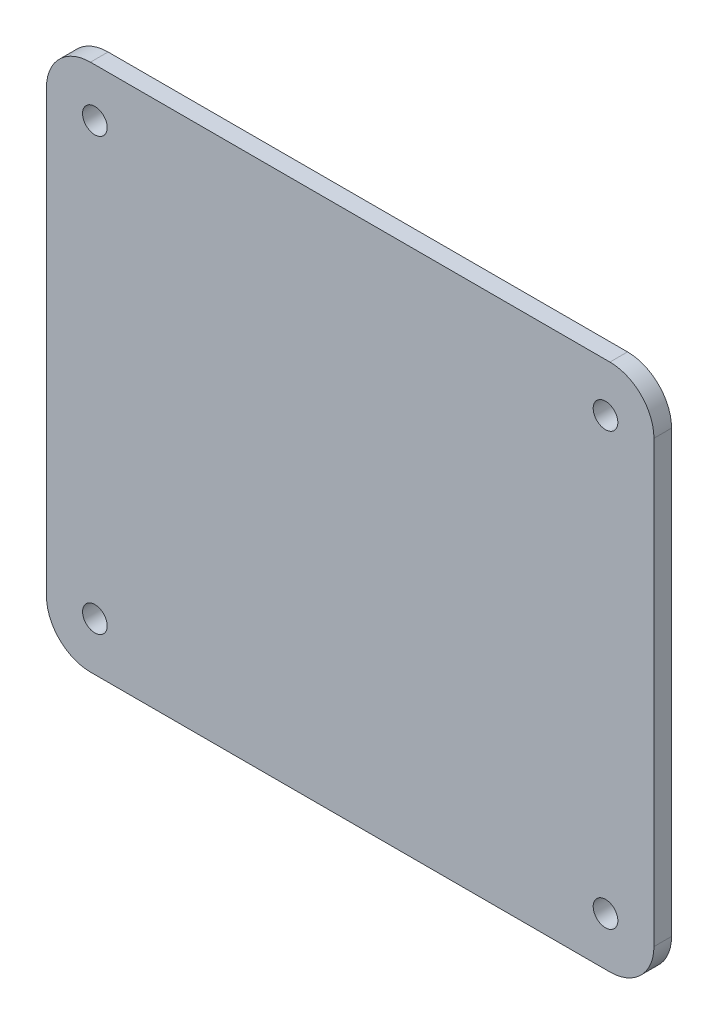
SolidWorks part; units mm, degrees
ref_plane "Front Plane" through (0, 0, 0) normal (0, 0, 1) x (1, 0, 0)
ref_plane "Top Plane" through (0, 0, 0) normal (0, 1, 0) x (1, 0, 0)
ref_plane "Right Plane" through (0, 0, 0) normal (1, 0, 0) x (0, 0, -1)
sketch3d "3DSketch1" plane through (0, 0, 0) normal (0, 0, 1) x (1, 0, 0)
sketch "Sketch3" plane through (0, 0, 55.2909) normal (0, 0, 1) x (1, 0, 0)
  line L20 (40.7272, 62.8578) -> (-18.2728, 62.8578)
  line L21 (-21.7728, 59.3578) -> (-21.7728, 9.3578)
  line L22 (-18.2728, 5.8578) -> (40.7272, 5.8578)
  line L23 (44.2272, 9.3578) -> (44.2272, 59.3578)
  line L24 (40.7272, 62.8578) -> (-18.2728, 62.8578)
  line L25 (-21.7728, 59.3578) -> (-21.7728, 9.3578)
  line L26 (-18.2728, 5.8578) -> (40.7272, 5.8578)
  line L27 (44.2272, 9.3578) -> (44.2272, 59.3578)
  line L44 (-23.2728, 59.3578) -> (-23.2728, 9.3578)
  line L45 (-18.2728, 4.3578) -> (40.7272, 4.3578)
  line L46 (45.7272, 9.3578) -> (45.7272, 59.3578)
  line L47 (40.7272, 64.3578) -> (-18.2728, 64.3578)
  line L48 (-23.2728, 59.3578) -> (-23.2728, 9.3578)
  line L49 (-18.2728, 4.3578) -> (40.7272, 4.3578)
  line L50 (45.7272, 9.3578) -> (45.7272, 59.3578)
  line L51 (40.7272, 64.3578) -> (-18.2728, 64.3578)
  arc A25 (-18.2728, 62.8578) -> (-21.7728, 59.3578) centre (-18.2728, 59.3578) ccw
  arc A26 (-21.7728, 9.3578) -> (-18.2728, 5.8578) centre (-18.2728, 9.3578) ccw
  arc A27 (40.7272, 5.8578) -> (44.2272, 9.3578) centre (40.7272, 9.3578) ccw
  arc A28 (44.2272, 59.3578) -> (40.7272, 62.8578) centre (40.7272, 59.3578) ccw
  arc A29 (-18.2728, 62.8578) -> (-21.7728, 59.3578) centre (-18.2728, 59.3578) ccw
  arc A30 (-21.7728, 9.3578) -> (-18.2728, 5.8578) centre (-18.2728, 9.3578) ccw
  arc A31 (40.7272, 5.8578) -> (44.2272, 9.3578) centre (40.7272, 9.3578) ccw
  arc A32 (44.2272, 59.3578) -> (40.7272, 62.8578) centre (40.7272, 59.3578) ccw
  arc A53 (-23.2728, 9.3578) -> (-18.2728, 4.3578) centre (-18.2728, 9.3578) ccw
  arc A54 (40.7272, 4.3578) -> (45.7272, 9.3578) centre (40.7272, 9.3578) ccw
  arc A55 (45.7272, 59.3578) -> (40.7272, 64.3578) centre (40.7272, 59.3578) ccw
  arc A56 (-18.2728, 64.3578) -> (-23.2728, 59.3578) centre (-18.2728, 59.3578) ccw
  arc A57 (-23.2728, 9.3578) -> (-18.2728, 4.3578) centre (-18.2728, 9.3578) ccw
  arc A58 (40.7272, 4.3578) -> (45.7272, 9.3578) centre (40.7272, 9.3578) ccw
  arc A59 (45.7272, 59.3578) -> (40.7272, 64.3578) centre (40.7272, 59.3578) ccw
  arc A60 (-18.2728, 64.3578) -> (-23.2728, 59.3578) centre (-18.2728, 59.3578) ccw
  dimension "D1" = 0.5
  dimension "D2" = 2
extrude "Boss-Extrude1" add sketch "Sketch3" along normal blind 6.5
sketch "Sketch5" plane through (0, 0, 55.2909) normal (0, 0, 1) x (1, 0, 0)
  line L0 (44.2272, 34.3578) -> (-21.7728, 34.3578) construction
  line L1 (44.2272, 9.3578) -> (44.2272, 59.3578) construction
  line L2 (-21.7728, 59.3578) -> (-21.7728, 9.3578) construction
  line L3 (11.2272, 62.8578) -> (11.2272, 5.8578) construction
  line L4 (40.7272, 62.8578) -> (-18.2728, 62.8578) construction
  line L5 (-18.2728, 5.8578) -> (40.7272, 5.8578) construction
  circle A0 centre (-17.7728, 58.8578) radius 3
  circle A1 centre (40.2272, 58.8578) radius 3
  circle A2 centre (-17.7728, 9.8578) radius 3
  circle A3 centre (40.2272, 9.8578) radius 3
  circle A4 centre (-17.7728, 9.8578) radius 1.4
  circle A5 centre (-17.7728, 58.8578) radius 1.4
  circle A6 centre (40.2272, 58.8578) radius 1.4
  circle A7 centre (40.2272, 9.8578) radius 1.4
sketch "Sketch6" plane through (0, 4.3578, 0) normal (0, -1, 0) x (1, 0, 0)
  line L0 (40.7272, 58.5409) -> (28.2272, 58.5409) construction
  line L1 (40.7272, 61.7909) -> (40.7272, 55.2909) construction
  line L2 (28.2272, 61.7909) -> (28.2272, 59.5909)
  line L3 (-18.2728, 61.7909) -> (40.7272, 61.7909) construction
  line L4 (28.2272, 59.5909) -> (36.2272, 59.5909)
  line L5 (40.7272, 61.5285) -> (32.2272, 61.5285) construction
  line L6 (36.2272, 59.5909) -> (36.2272, 61.7909)
  line L7 (36.2272, 61.7909) -> (28.2272, 61.7909)
sketch "Sketch7" plane through (0, 4.3578, 0) normal (0, -1, 0) x (1, 0, 0)
  line L0 (-18.2728, 58.5409) -> (18.7272, 58.5409) construction
  line L1 (-18.2728, 61.7909) -> (-18.2728, 55.2909) construction
  line L7 (18.7272, 61.7909) -> (18.7272, 59.7909)
  line L8 (18.7272, 59.7909) -> (2.7272, 59.7909)
  line L9 (2.7272, 59.7909) -> (2.7272, 61.7909)
  line L10 (-18.2728, 61.7909) -> (40.7272, 61.7909) construction
  line L11 (2.7272, 61.7909) -> (18.7272, 61.7909)
sketch "Sketch8" plane through (0, 4.3578, 0) normal (0, -1, 0) x (1, 0, 0)
  line L0 (-18.2728, 58.5409) -> (-6.1728, 58.5409) construction
  line L1 (-18.2728, 61.7909) -> (-18.2728, 55.2909) construction
  line L7 (-6.1728, 61.7909) -> (-6.1728, 58.9909)
  line L8 (-18.2728, 61.7909) -> (40.7272, 61.7909) construction
  line L9 (-6.1728, 58.9909) -> (-15.1728, 58.9909)
  line L10 (-15.1728, 58.9909) -> (-15.1728, 61.7909)
  line L11 (-15.1728, 61.7909) -> (-6.1728, 61.7909)
sketch "Sketch9" plane through (45.7272, 0, 0) normal (1, 0, 0) x (0, 0, -1)
  line L0 (-58.5409, 9.3578) -> (-58.5409, 45.8078) construction
  line L1 (-61.7909, 9.3578) -> (-55.2909, 9.3578) construction
  line L3 (-59.7909, 45.3078) -> (-59.7909, 29.8078)
  line L9 (-59.7909, 29.8078) -> (-61.7909, 29.8078)
  line L10 (-61.7909, 9.3578) -> (-61.7909, 59.3578) construction
  line L12 (-61.7909, 45.3078) -> (-59.7909, 45.3078)
  line L13 (-61.7909, 45.3078) -> (-61.7909, 29.8078)
sketch "Sketch10" plane through (-23.2728, 0, 0) normal (-1, 0, 0) x (0, 0, 1)
  line L0 (58.5409, 9.3578) -> (58.5409, 42.6578) construction
  line L1 (61.7909, 9.3578) -> (55.2909, 9.3578) construction
  line L2 (55.2909, 42.6578) -> (59.2909, 42.6578)
  line L3 (55.2909, 59.3578) -> (55.2909, 9.3578) construction
  line L4 (59.2909, 42.6578) -> (59.2909, 26.6578)
  line L5 (59.2909, 26.6578) -> (55.2909, 26.6578)
  line L6 (55.2909, 26.6578) -> (55.2909, 42.6578)
sketch "Sketch11" plane through (0, 0, 55.2909) normal (0, 0, 1) x (1, 0, 0)
  line L25 (-23.2728, 26.6578) -> (-23.2728, 42.6578)
  line L30 (-23.2728, 26.6578) -> (-23.2728, 9.3578)
  line L31 (-18.2728, 4.3578) -> (40.7272, 4.3578)
  line L32 (-23.2728, 59.3578) -> (-23.2728, 42.6578)
  line L33 (40.7272, 64.3578) -> (-18.2728, 64.3578)
  line L34 (45.7272, 9.3578) -> (45.7272, 59.3578)
  line L35 (-23.2728, 26.6578) -> (-23.2728, 9.3578)
  line L36 (-18.2728, 4.3578) -> (40.7272, 4.3578)
  line L37 (-23.2728, 59.3578) -> (-23.2728, 42.6578)
  line L38 (40.7272, 64.3578) -> (-18.2728, 64.3578)
  line L39 (45.7272, 9.3578) -> (45.7272, 59.3578)
  arc A31 (-23.2728, 9.3578) -> (-18.2728, 4.3578) centre (-18.2728, 9.3578) ccw
  arc A32 (-18.2728, 64.3578) -> (-23.2728, 59.3578) centre (-18.2728, 59.3578) ccw
  arc A33 (45.7272, 59.3578) -> (40.7272, 64.3578) centre (40.7272, 59.3578) ccw
  arc A34 (40.7272, 4.3578) -> (45.7272, 9.3578) centre (40.7272, 9.3578) ccw
  arc A35 (-23.2728, 9.3578) -> (-18.2728, 4.3578) centre (-18.2728, 9.3578) ccw
  arc A36 (-18.2728, 64.3578) -> (-23.2728, 59.3578) centre (-18.2728, 59.3578) ccw
  arc A37 (45.7272, 59.3578) -> (40.7272, 64.3578) centre (40.7272, 59.3578) ccw
  arc A38 (40.7272, 4.3578) -> (45.7272, 9.3578) centre (40.7272, 9.3578) ccw
  dimension "D1" = 0
extrude "Boss-Extrude5" add sketch "Sketch5" along normal blind 3.2 separate body
sketch "Sketch13" plane through (0, 0, 55.2909) normal (0, 0, 1) x (1, 0, 0)
  line L21 (-23.2728, 26.6578) -> (-23.2728, 42.6578)
  line L26 (-23.2728, 26.6578) -> (-23.2728, 9.3578)
  line L27 (-23.2728, 59.3578) -> (-23.2728, 42.6578)
  line L28 (40.7272, 64.3578) -> (-18.2728, 64.3578)
  line L29 (45.7272, 9.3578) -> (45.7272, 59.3578)
  line L30 (-18.2728, 4.3578) -> (40.7272, 4.3578)
  line L31 (-23.2728, 26.6578) -> (-23.2728, 9.3578)
  line L32 (-23.2728, 59.3578) -> (-23.2728, 42.6578)
  line L33 (40.7272, 64.3578) -> (-18.2728, 64.3578)
  line L34 (45.7272, 9.3578) -> (45.7272, 59.3578)
  line L35 (-18.2728, 4.3578) -> (40.7272, 4.3578)
  arc A28 (-18.2728, 64.3578) -> (-23.2728, 59.3578) centre (-18.2728, 59.3578) ccw
  arc A29 (45.7272, 59.3578) -> (40.7272, 64.3578) centre (40.7272, 59.3578) ccw
  arc A30 (40.7272, 4.3578) -> (45.7272, 9.3578) centre (40.7272, 9.3578) ccw
  arc A31 (-23.2728, 9.3578) -> (-18.2728, 4.3578) centre (-18.2728, 9.3578) ccw
  arc A32 (-18.2728, 64.3578) -> (-23.2728, 59.3578) centre (-18.2728, 59.3578) ccw
  arc A33 (45.7272, 59.3578) -> (40.7272, 64.3578) centre (40.7272, 59.3578) ccw
  arc A34 (40.7272, 4.3578) -> (45.7272, 9.3578) centre (40.7272, 9.3578) ccw
  arc A35 (-23.2728, 9.3578) -> (-18.2728, 4.3578) centre (-18.2728, 9.3578) ccw
  dimension "D1" = 0
extrude "Boss-Extrude6" add sketch "Sketch13" against normal blind 1.5
sketch "Sketch17" plane through (0, 0, 55.2909) normal (0, 0, 1) x (1, 0, 0)
  line L0 (44.2272, 34.3578) -> (-21.9476, 34.3578) construction
  line L1 (44.2272, 9.3578) -> (44.2272, 59.3578) construction
  line L2 (11.2272, 5.8578) -> (11.2272, 62.8578) construction
  line L3 (-18.2728, 5.8578) -> (40.7272, 5.8578) construction
  line L4 (40.7272, 62.8578) -> (-18.2728, 62.8578) construction
  circle A0 centre (40.2272, 9.8578) radius 1.4
  circle A1 centre (-17.7728, 9.8578) radius 1.4
  circle A2 centre (-17.7728, 58.8578) radius 1.4
  circle A3 centre (40.2272, 58.8578) radius 1.4
extrude "Cut-Extrude9" cut sketch "Sketch17" against normal blind 1.5
sketch "Sketch18" plane through (0, 0, 58.4909) normal (0, 0, 1) x (1, 0, 0)
  line L1 (67.9798, -11.5209) -> (-50.5034, -11.5209)
  line L2 (67.9798, -11.5209) -> (67.9798, 101.5715)
  line L3 (67.9798, 101.5715) -> (-50.5034, 101.5715)
  line L4 (-50.5034, -11.5209) -> (-50.5034, 101.5715)
extrude "Cut-Extrude10" cut sketch "Sketch18" against normal blind 4 and the other way blind 10
sketch "Sketch19" plane through (0, 0, 53.7909) normal (0, 0, -1) x (-1, 0, 0)
  line L8 (-40.7272, 64.3578) -> (18.2728, 64.3578) construction
  line L9 (-35.7272, 54.3578) -> (-30.7272, 54.3578)
  line L10 (-35.7272, 54.3578) -> (-35.7272, 49.3578)
  line L11 (-35.7272, 49.3578) -> (-30.7272, 49.3578)
  line L12 (-30.7272, 54.3578) -> (-30.7272, 49.3578)
  line L13 (8.2728, 19.3578) -> (13.2728, 19.3578)
  line L14 (8.2728, 19.3578) -> (8.2728, 14.3578)
  line L15 (8.2728, 14.3578) -> (13.2728, 14.3578)
  line L16 (13.2728, 19.3578) -> (13.2728, 14.3578)
  line L17 (8.2728, 54.3578) -> (13.2728, 54.3578)
  line L18 (8.2728, 54.3578) -> (8.2728, 49.3578)
  line L19 (8.2728, 49.3578) -> (13.2728, 49.3578)
  line L20 (13.2728, 54.3578) -> (13.2728, 49.3578)
  line L21 (-35.7272, 19.3578) -> (-30.7272, 19.3578)
  line L22 (-35.7272, 19.3578) -> (-35.7272, 14.3578)
  line L23 (-35.7272, 14.3578) -> (-30.7272, 14.3578)
  line L24 (-30.7272, 19.3578) -> (-30.7272, 14.3578)
  line L25 (-45.7272, 9.3578) -> (-45.7272, 59.3578) construction
  line L26 (23.2728, 59.3578) -> (23.2728, 9.3578) construction
  line L27 (18.2728, 4.3578) -> (-40.7272, 4.3578) construction
  dimension "D1" = 5
  dimension "D2" = 5
  dimension "D3" = 5
  dimension "D4" = 5
  dimension "D5" = 5
  dimension "D6" = 5
  dimension "D7" = 5
  dimension "D8" = 5
  dimension "D9" = 10
  dimension "D10" = 10
  dimension "D11" = 10
  dimension "D12" = 10
extrude "Boss-Extrude9" add sketch "Sketch19" along normal blind 7
sketch "Sketch20" plane through (0, 0, 54.4909) normal (0, 0, 1) x (1, 0, 0)
  line L0 (45.7272, 9.3578) -> (45.7272, 59.3578) construction
  line L1 (45.7272, 4.3578) -> (-23.2728, 4.3578)
  line L2 (45.7272, 4.3578) -> (45.7272, 64.3578)
  line L3 (45.7272, 64.3578) -> (-23.2728, 64.3578)
  line L4 (-23.2728, 4.3578) -> (-23.2728, 64.3578)
  line L5 (40.7272, 64.3578) -> (-18.2728, 64.3578) construction
  line L6 (-23.2728, 59.3578) -> (-23.2728, 9.3578) construction
  line L7 (-18.2728, 4.3578) -> (40.7272, 4.3578) construction
  line L8 (45.7272, 9.3578) -> (45.7272, 59.3578)
  arc A0 (45.7272, 9.3578) -> (40.7272, 4.3578) centre (40.7272, 9.3578) cw
  arc A1 (45.7272, 59.3578) -> (40.7272, 64.3578) centre (40.7272, 59.3578) ccw
  arc A2 (-23.2728, 59.3578) -> (-18.2728, 64.3578) centre (-18.2728, 59.3578) cw
  arc A3 (-23.2728, 9.3578) -> (-18.2728, 4.3578) centre (-18.2728, 9.3578) ccw
  arc A4 (-23.2728, 9.3578) -> (-18.2728, 4.3578) centre (-18.2728, 9.3578) ccw construction
  circle M5 centre (40.2272, 9.8578) radius 1.4
  circle M6 centre (-17.7728, 9.8578) radius 1.4
  circle M7 centre (40.2272, 58.8578) radius 1.4
  circle M8 centre (-17.7728, 58.8578) radius 1.4
  arc M9 (-18.2728, 64.3578) -> (-23.2728, 59.3578) centre (-18.2728, 59.3578) ccw
  line M10 (-23.2728, 59.3578) -> (-23.2728, 9.3578)
  arc M11 (-23.2728, 9.3578) -> (-18.2728, 4.3578) centre (-18.2728, 9.3578) ccw
  line M12 (-18.2728, 4.3578) -> (40.7272, 4.3578)
  arc M13 (40.7272, 4.3578) -> (45.7272, 9.3578) centre (40.7272, 9.3578) ccw
  line M14 (45.7272, 9.3578) -> (45.7272, 59.3578)
  arc M15 (45.7272, 59.3578) -> (40.7272, 64.3578) centre (40.7272, 59.3578) ccw
  line M16 (40.7272, 64.3578) -> (-18.2728, 64.3578)
extrude "Boss-Extrude10" add sketch "Sketch20" along normal blind 1.3 contours M16 M9 M10 M11 M12 M13 M14 M15 M6 M8 M7 M5
